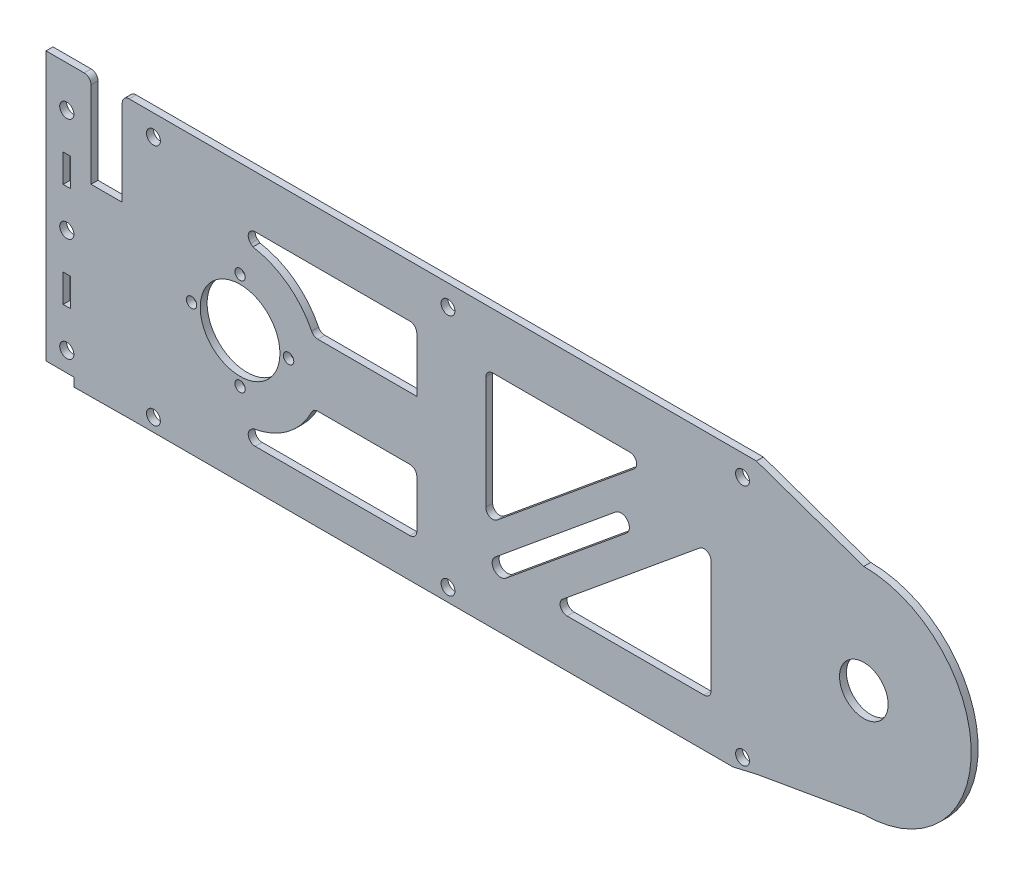
SolidWorks part; units mm, degrees
ref_plane "前视基准面" through (0, 0, 0) normal (0, 0, 1) x (1, 0, 0)
ref_plane "上视基准面" through (0, 0, 0) normal (0, 1, 0) x (1, 0, 0)
ref_plane "右视基准面" through (0, 0, 0) normal (1, 0, 0) x (0, 0, -1)
sketch "草图1" plane through (0, 0, 0) normal (0, 0, 1) x (1, 0, 0)
  line L0 (1.6429, 32.0043) -> (1.6429, 27.9043)
  line L1 (1.6429, 18.9543) -> (1.6429, 10.9543) construction
  line L2 (0.5929, 10.9043) -> (2.6929, 10.9043)
  line L3 (0.5929, 10.9043) -> (0.5929, 19.0043)
  line L4 (0.5929, 19.0043) -> (2.6929, 19.0043)
  line L5 (2.6929, 10.9043) -> (2.6929, 19.0043)
  line L6 (0.5929, 10.9043) -> (2.6929, 19.0043) construction
  line L7 (0.5929, 19.0043) -> (2.6929, 10.9043) construction
  line L12 (1.6429, -0.0457) -> (-4.3571, -0.0457) construction
  line L13 (-4.3571, -0.0457) -> (-4.3571, 41.8043)
  line L14 (-4.3571, 41.8043) -> (262.6429, 41.8043) construction
  line L15 (262.6429, 41.8043) -> (262.6429, -38.1957) construction
  line L18 (51.6429, -0.0457) -> (97.8433, -0.0457) construction
  line L19 (51.6429, -0.0457) -> (231.6429, -0.0457) construction
  line L21 (200.6429, -0.0457) -> (200.6429, 41.8043) construction
  line L23 (200.6429, 41.8043) -> (231.6429, 30.9543)
  line L26 (231.6429, -31.0457) -> (200.6561, -36.4559)
  line L28 (-4.3571, 41.8043) -> (8.6429, 41.8043)
  line L29 (1.6429, -0.0457) -> (37.6429, -0.0457) construction
  line L32 (22.4658, -38.0457) -> (193.8469, -38.0457)
  line L42 (17.6429, 14.9543) -> (17.6429, 41.8043)
  line L43 (17.6429, 41.8043) -> (200.6429, 41.8043)
  line L44 (8.6429, 41.8043) -> (8.6429, 14.9543)
  line L45 (8.6429, 14.9543) -> (17.6429, 14.9543)
  line L47 (193.8469, -38.0457) -> (200.6561, -36.4559)
  line L48 (0.5929, -19.0957) -> (2.6929, -10.9957) construction
  line L49 (0.5929, -10.9957) -> (2.6929, -19.0957) construction
  line L50 (1.6429, -19.0457) -> (1.6429, -11.0457) construction
  line L51 (2.6929, -10.9957) -> (2.6929, -19.0957)
  line L52 (0.5929, -19.0957) -> (2.6929, -19.0957)
  line L53 (0.5929, -10.9957) -> (0.5929, -19.0957)
  line L54 (0.5929, -10.9957) -> (2.6929, -10.9957)
  line L55 (-4.3571, -35.7026) -> (3.7929, -35.7026)
  line L56 (3.7929, -35.7026) -> (3.7929, -38.1957)
  line L57 (3.7929, -38.1957) -> (22.4658, -38.0457)
  line L58 (-4.3571, -35.7026) -> (-4.3571, -0.0457)
  circle A0 centre (1.6429, 29.9543) radius 2.05
  circle A1 centre (1.6429, -0.0457) radius 2.05
  circle A2 centre (1.6429, -30.0457) radius 2.05
  circle A3 centre (51.6429, -0.0457) radius 11.5
  circle A4 centre (51.6429, -0.0457) radius 14 construction
  circle A5 centre (51.6429, -14.0457) radius 1.5
  circle A12 centre (37.6429, -0.0457) radius 1.5
  circle A13 centre (51.6429, 13.9543) radius 1.5
  circle A14 centre (65.6429, -0.0457) radius 1.5
  circle A15 centre (231.6429, -0.0457) radius 7.02
  circle A16 centre (231.6429, -0.0457) radius 31 construction
  arc A17 (231.6429, 30.9543) -> (231.6429, -31.0457) centre (231.6429, -0.0457) cw
  point P6 (1.6429, 14.9543)
  point P56 (1.6429, -15.0457)
  dimension "D3" = 23
  dimension "D4" = 4
  dimension "D13" = 14.04
  dimension "D1" = 8.1
  dimension "D2" = 2.1
  dimension "D5" = 50
  dimension "D7" = 15
  dimension "D8" = 60
  dimension "D9" = 30
  dimension "D11" = 41.85
  dimension "D12" = 31
  dimension "D14" = 180
  dimension "D17" = 13
extrude "凸台-拉伸1" add sketch "草图1" along normal blind 2
sketch "草图2" plane through (0, 0, 2) normal (0, 0, 1) x (1, 0, 0)
  line L0 (111.6429, -34.2457) -> (196.6429, 35.7543) construction
  line L1 (196.6429, 35.7543) -> (196.6429, -34.2457) construction
  line L2 (196.6429, -34.2457) -> (111.6429, -34.2457) construction
  line L3 (187.5429, -24.2457) -> (140.4162, -24.2457)
  line L4 (140.4162, -24.2457) -> (187.5429, 14.5645)
  line L5 (187.5429, 14.5645) -> (187.5429, -24.2457)
  line L6 (111.6429, -34.2457) -> (111.6429, 35.7543) construction
  line L7 (111.6429, 35.7543) -> (196.6429, 35.7543) construction
  line L8 (122.5429, 25.7543) -> (169.6695, 25.7543)
  line L9 (122.5429, -13.0559) -> (169.6695, 25.7543)
  line L10 (122.5429, -13.0559) -> (122.5429, 25.7543)
  line L11 (26.6429, 35.7543) -> (51.6429, 13.9543) construction
  line L13 (65.6429, -0.0457) -> (111.6429, -0.0457) construction
  line L18 (17.6429, 41.8043) -> (200.6429, 41.8043) construction
  line L19 (17.6429, 14.9543) -> (17.6429, 41.8043) construction
  line L20 (126.8224, -21.7449) -> (161.5593, 6.8619) construction
  line L23 (26.6429, 35.7543) -> (111.6429, 35.7543) construction
  line L24 (111.6429, -0.0457) -> (111.6429, 35.7543) construction
  line L25 (72.8089, 8.9543) -> (102.6429, 8.9543)
  line L26 (102.6429, 8.9543) -> (102.6429, 26.7543)
  line L27 (50.6579, 26.7543) -> (102.6429, 26.7543)
  line L28 (50.6579, 26.7543) -> (55.3631, 22.6514)
  line L29 (102.6429, -9.0457) -> (102.6429, -26.8457)
  line L30 (72.8089, -9.0457) -> (102.6429, -9.0457)
  line L31 (50.6579, -26.8457) -> (55.3631, -22.7429)
  line L32 (50.6579, -26.8457) -> (102.6429, -26.8457)
  line L38 (125.279, -19.8708) -> (160.0159, 8.7361)
  line L39 (128.3658, -23.619) -> (163.1027, 4.9878)
  circle A0 centre (26.6429, 35.7543) radius 2
  circle A1 centre (111.6429, 35.7543) radius 2
  circle A2 centre (196.6429, 35.7543) radius 2
  circle A3 centre (111.6429, -34.2457) radius 2
  circle A4 centre (196.6429, -34.2457) radius 2
  circle A5 centre (26.6429, -34.2457) radius 2
  arc A8 (51.6429, 13.9543) -> (65.6429, -0.0457) centre (51.6429, -0.0457) cw construction
  arc A9 (55.3631, 22.6514) -> (72.8089, 8.9543) centre (51.6429, -0.0457) cw
  arc A10 (55.3631, -22.7429) -> (72.8089, -9.0457) centre (51.6429, -0.0457) ccw
  arc A11 (125.279, -19.8708) -> (128.3658, -23.619) centre (126.8224, -21.7449) ccw
  arc A12 (163.1027, 4.9878) -> (160.0159, 8.7361) centre (161.5593, 6.8619) ccw
  point P24 (26.6429, 35.8043)
  point P31 (144.1908, -7.4415)
  point P42 (0, 0)
  point P43 (0, 0)
  dimension "D3" = 9
  dimension "D4" = 9
  dimension "D1" = 6
  dimension "D2" = 9
  dimension "D5" = 85
  dimension "D6" = 85
  dimension "D7" = 70
extrude "切除-拉伸1" cut sketch "草图2" against normal blind 4
fillet "圆角1" radius 2 15 edges at (187.5429, -24.2457, 1) (140.4162, -24.2457, 1) (187.5429, 14.5645, 1) (169.6695, 25.7543, 1) (122.5429, -13.0559, 1) (122.5429, 25.7543, 1) (72.8089, 8.9543, 1) (72.8089, -9.0457, 1) (50.6579, -26.8457, 1) (102.6429, -26.8457, 1) (50.6579, 26.7543, 1) (102.6429, 26.7543, 1) (102.6429, -9.0457, 1) (17.6429, 41.8043, 1) (8.6429, 41.8043, 1)
